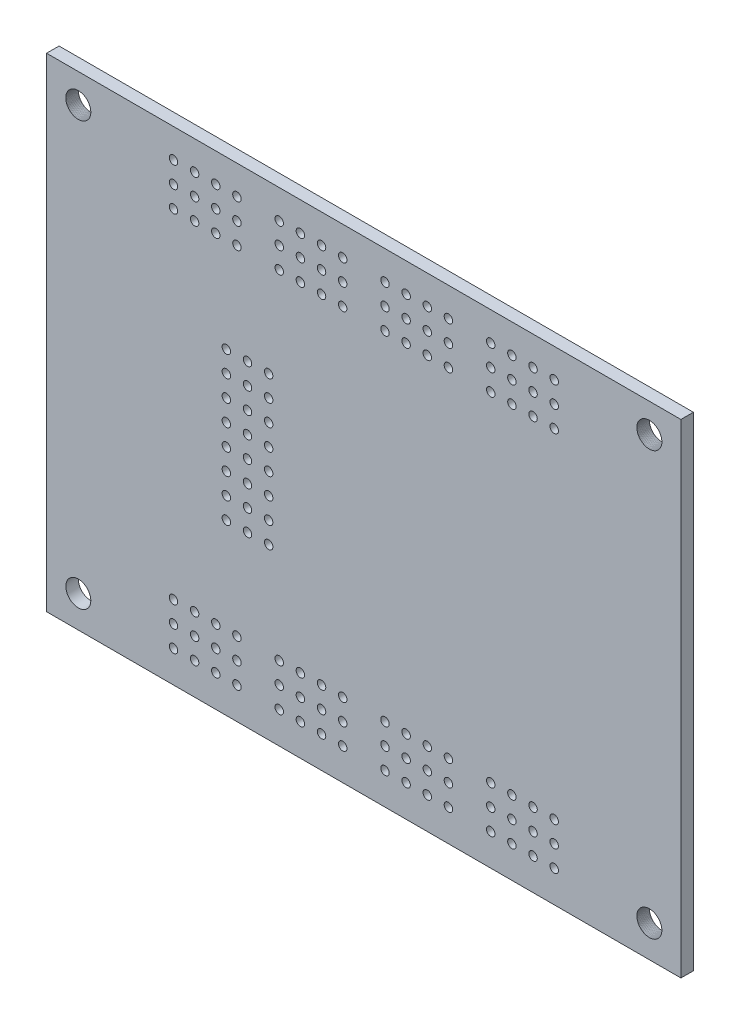
SolidWorks part; units mm, degrees
ref_plane "Front Plane" through (0, 0, 0) normal (0, 0, 1) x (1, 0, 0)
ref_plane "Top Plane" through (0, 0, 0) normal (0, 1, 0) x (1, 0, 0)
ref_plane "Right Plane" through (0, 0, 0) normal (1, 0, 0) x (0, 0, -1)
ref_plane "Plane1" through (0, 0, 1.5) normal (0, 0, 1) x (1, 0, 0)
sketch "Sketch1" plane through (0, 0, 1.5) normal (0, 0, 1) x (1, 0, 0)
  line L0 (0, 58.09) -> (0, 0)
  line L1 (0, 0) -> (76.18, 0)
  line L2 (76.18, 0) -> (76.18, 58.09)
  line L3 (76.18, 58.09) -> (0, 58.09)
  line L4 (5.3024, 54.7704) -> (5.31, 54.6636)
  line L5 (5.31, 54.6636) -> (5.31, 54.5564)
  line L6 (5.31, 54.5564) -> (5.3024, 54.4496)
  line L7 (5.3024, 54.4496) -> (5.2871, 54.3435)
  line L8 (5.2871, 54.3435) -> (5.2643, 54.2388)
  line L9 (5.2643, 54.2388) -> (5.2341, 54.136)
  line L10 (5.2341, 54.136) -> (5.1967, 54.0356)
  line L11 (5.1967, 54.0356) -> (5.1522, 53.9381)
  line L12 (5.1522, 53.9381) -> (5.1008, 53.8441)
  line L13 (5.1008, 53.8441) -> (5.0429, 53.754)
  line L14 (5.0429, 53.754) -> (4.9787, 53.6682)
  line L15 (4.9787, 53.6682) -> (4.9085, 53.5872)
  line L16 (4.9085, 53.5872) -> (4.8328, 53.5115)
  line L17 (4.8328, 53.5115) -> (4.7518, 53.4413)
  line L18 (4.7518, 53.4413) -> (4.666, 53.3771)
  line L19 (4.666, 53.3771) -> (4.5759, 53.3192)
  line L20 (4.5759, 53.3192) -> (4.4818, 53.2678)
  line L21 (4.4818, 53.2678) -> (4.3844, 53.2233)
  line L22 (4.3844, 53.2233) -> (4.284, 53.1859)
  line L23 (4.284, 53.1859) -> (4.1812, 53.1557)
  line L24 (4.1812, 53.1557) -> (4.0765, 53.1329)
  line L25 (4.0765, 53.1329) -> (3.9704, 53.1176)
  line L26 (3.9704, 53.1176) -> (3.8636, 53.11)
  line L27 (3.8636, 53.11) -> (3.7564, 53.11)
  line L28 (3.7564, 53.11) -> (3.6496, 53.1176)
  line L29 (3.6496, 53.1176) -> (3.5435, 53.1329)
  line L30 (3.5435, 53.1329) -> (3.4388, 53.1557)
  line L31 (3.4388, 53.1557) -> (3.336, 53.1859)
  line L32 (3.336, 53.1859) -> (3.2356, 53.2233)
  line L33 (3.2356, 53.2233) -> (3.1381, 53.2678)
  line L34 (3.1381, 53.2678) -> (3.0441, 53.3192)
  line L35 (3.0441, 53.3192) -> (2.954, 53.3771)
  line L36 (2.954, 53.3771) -> (2.8682, 53.4413)
  line L37 (2.8682, 53.4413) -> (2.7872, 53.5115)
  line L38 (2.7872, 53.5115) -> (2.7115, 53.5872)
  line L39 (2.7115, 53.5872) -> (2.6413, 53.6682)
  line L40 (2.6413, 53.6682) -> (2.5771, 53.754)
  line L41 (2.5771, 53.754) -> (2.5192, 53.8441)
  line L42 (2.5192, 53.8441) -> (2.4678, 53.9381)
  line L43 (2.4678, 53.9381) -> (2.4233, 54.0356)
  line L44 (2.4233, 54.0356) -> (2.3859, 54.136)
  line L45 (2.3859, 54.136) -> (2.3557, 54.2388)
  line L46 (2.3557, 54.2388) -> (2.3329, 54.3435)
  line L47 (2.3329, 54.3435) -> (2.3176, 54.4496)
  line L48 (2.3176, 54.4496) -> (2.31, 54.5564)
  line L49 (2.31, 54.5564) -> (2.31, 54.6636)
  line L50 (2.31, 54.6636) -> (2.3176, 54.7704)
  line L51 (2.3176, 54.7704) -> (2.3329, 54.8765)
  line L52 (2.3329, 54.8765) -> (2.3557, 54.9812)
  line L53 (2.3557, 54.9812) -> (2.3859, 55.084)
  line L54 (2.3859, 55.084) -> (2.4233, 55.1844)
  line L55 (2.4233, 55.1844) -> (2.4678, 55.2819)
  line L56 (2.4678, 55.2819) -> (2.5192, 55.3759)
  line L57 (2.5192, 55.3759) -> (2.5771, 55.466)
  line L58 (2.5771, 55.466) -> (2.6413, 55.5518)
  line L59 (2.6413, 55.5518) -> (2.7115, 55.6328)
  line L60 (2.7115, 55.6328) -> (2.7872, 55.7085)
  line L61 (2.7872, 55.7085) -> (2.8682, 55.7787)
  line L62 (2.8682, 55.7787) -> (2.954, 55.8429)
  line L63 (2.954, 55.8429) -> (3.0441, 55.9008)
  line L64 (3.0441, 55.9008) -> (3.1381, 55.9522)
  line L65 (3.1381, 55.9522) -> (3.2356, 55.9967)
  line L66 (3.2356, 55.9967) -> (3.336, 56.0341)
  line L67 (3.336, 56.0341) -> (3.4388, 56.0643)
  line L68 (3.4388, 56.0643) -> (3.5435, 56.0871)
  line L69 (3.5435, 56.0871) -> (3.6496, 56.1024)
  line L70 (3.6496, 56.1024) -> (3.7564, 56.11)
  line L71 (3.7564, 56.11) -> (3.8636, 56.11)
  line L72 (3.8636, 56.11) -> (3.9704, 56.1024)
  line L73 (3.9704, 56.1024) -> (4.0765, 56.0871)
  line L74 (4.0765, 56.0871) -> (4.1812, 56.0643)
  line L75 (4.1812, 56.0643) -> (4.284, 56.0341)
  line L76 (4.284, 56.0341) -> (4.3844, 55.9967)
  line L77 (4.3844, 55.9967) -> (4.4818, 55.9522)
  line L78 (4.4818, 55.9522) -> (4.5759, 55.9008)
  line L79 (4.5759, 55.9008) -> (4.666, 55.8429)
  line L80 (4.666, 55.8429) -> (4.7518, 55.7787)
  line L81 (4.7518, 55.7787) -> (4.8328, 55.7085)
  line L82 (4.8328, 55.7085) -> (4.9085, 55.6328)
  line L83 (4.9085, 55.6328) -> (4.9787, 55.5518)
  line L84 (4.9787, 55.5518) -> (5.0429, 55.466)
  line L85 (5.0429, 55.466) -> (5.1008, 55.3759)
  line L86 (5.1008, 55.3759) -> (5.1522, 55.2819)
  line L87 (5.1522, 55.2819) -> (5.1967, 55.1844)
  line L88 (5.1967, 55.1844) -> (5.2341, 55.084)
  line L89 (5.2341, 55.084) -> (5.2643, 54.9812)
  line L90 (5.2643, 54.9812) -> (5.2871, 54.8765)
  line L91 (5.2871, 54.8765) -> (5.3024, 54.7704)
  line L92 (73.8824, 54.7704) -> (73.89, 54.6636)
  line L93 (73.89, 54.6636) -> (73.89, 54.5564)
  line L94 (73.89, 54.5564) -> (73.8824, 54.4496)
  line L95 (73.8824, 54.4496) -> (73.8671, 54.3435)
  line L96 (73.8671, 54.3435) -> (73.8443, 54.2388)
  line L97 (73.8443, 54.2388) -> (73.8141, 54.136)
  line L98 (73.8141, 54.136) -> (73.7767, 54.0356)
  line L99 (73.7767, 54.0356) -> (73.7322, 53.9381)
  line L100 (73.7322, 53.9381) -> (73.6808, 53.8441)
  line L101 (73.6808, 53.8441) -> (73.6229, 53.754)
  line L102 (73.6229, 53.754) -> (73.5587, 53.6682)
  line L103 (73.5587, 53.6682) -> (73.4885, 53.5872)
  line L104 (73.4885, 53.5872) -> (73.4128, 53.5115)
  line L105 (73.4128, 53.5115) -> (73.3318, 53.4413)
  line L106 (73.3318, 53.4413) -> (73.246, 53.3771)
  line L107 (73.246, 53.3771) -> (73.1559, 53.3192)
  line L108 (73.1559, 53.3192) -> (73.0619, 53.2678)
  line L109 (73.0619, 53.2678) -> (72.9644, 53.2233)
  line L110 (72.9644, 53.2233) -> (72.864, 53.1859)
  line L111 (72.864, 53.1859) -> (72.7612, 53.1557)
  line L112 (72.7612, 53.1557) -> (72.6565, 53.1329)
  line L113 (72.6565, 53.1329) -> (72.5504, 53.1176)
  line L114 (72.5504, 53.1176) -> (72.4436, 53.11)
  line L115 (72.4436, 53.11) -> (72.3364, 53.11)
  line L116 (72.3364, 53.11) -> (72.2296, 53.1176)
  line L117 (72.2296, 53.1176) -> (72.1235, 53.1329)
  line L118 (72.1235, 53.1329) -> (72.0188, 53.1557)
  line L119 (72.0188, 53.1557) -> (71.916, 53.1859)
  line L120 (71.916, 53.1859) -> (71.8156, 53.2233)
  line L121 (71.8156, 53.2233) -> (71.7181, 53.2678)
  line L122 (71.7181, 53.2678) -> (71.6241, 53.3192)
  line L123 (71.6241, 53.3192) -> (71.534, 53.3771)
  line L124 (71.534, 53.3771) -> (71.4482, 53.4413)
  line L125 (71.4482, 53.4413) -> (71.3672, 53.5115)
  line L126 (71.3672, 53.5115) -> (71.2915, 53.5872)
  line L127 (71.2915, 53.5872) -> (71.2213, 53.6682)
  line L128 (71.2213, 53.6682) -> (71.1571, 53.754)
  line L129 (71.1571, 53.754) -> (71.0992, 53.8441)
  line L130 (71.0992, 53.8441) -> (71.0478, 53.9381)
  line L131 (71.0478, 53.9381) -> (71.0033, 54.0356)
  line L132 (71.0033, 54.0356) -> (70.9659, 54.136)
  line L133 (70.9659, 54.136) -> (70.9357, 54.2388)
  line L134 (70.9357, 54.2388) -> (70.9129, 54.3435)
  line L135 (70.9129, 54.3435) -> (70.8976, 54.4496)
  line L136 (70.8976, 54.4496) -> (70.89, 54.5564)
  line L137 (70.89, 54.5564) -> (70.89, 54.6636)
  line L138 (70.89, 54.6636) -> (70.8976, 54.7704)
  line L139 (70.8976, 54.7704) -> (70.9129, 54.8765)
  line L140 (70.9129, 54.8765) -> (70.9357, 54.9812)
  line L141 (70.9357, 54.9812) -> (70.9659, 55.084)
  line L142 (70.9659, 55.084) -> (71.0033, 55.1844)
  line L143 (71.0033, 55.1844) -> (71.0478, 55.2819)
  line L144 (71.0478, 55.2819) -> (71.0992, 55.3759)
  line L145 (71.0992, 55.3759) -> (71.1571, 55.466)
  line L146 (71.1571, 55.466) -> (71.2213, 55.5518)
  line L147 (71.2213, 55.5518) -> (71.2915, 55.6328)
  line L148 (71.2915, 55.6328) -> (71.3672, 55.7085)
  line L149 (71.3672, 55.7085) -> (71.4482, 55.7787)
  line L150 (71.4482, 55.7787) -> (71.534, 55.8429)
  line L151 (71.534, 55.8429) -> (71.6241, 55.9008)
  line L152 (71.6241, 55.9008) -> (71.7181, 55.9522)
  line L153 (71.7181, 55.9522) -> (71.8156, 55.9967)
  line L154 (71.8156, 55.9967) -> (71.916, 56.0341)
  line L155 (71.916, 56.0341) -> (72.0188, 56.0643)
  line L156 (72.0188, 56.0643) -> (72.1235, 56.0871)
  line L157 (72.1235, 56.0871) -> (72.2296, 56.1024)
  line L158 (72.2296, 56.1024) -> (72.3364, 56.11)
  line L159 (72.3364, 56.11) -> (72.4436, 56.11)
  line L160 (72.4436, 56.11) -> (72.5504, 56.1024)
  line L161 (72.5504, 56.1024) -> (72.6565, 56.0871)
  line L162 (72.6565, 56.0871) -> (72.7612, 56.0643)
  line L163 (72.7612, 56.0643) -> (72.864, 56.0341)
  line L164 (72.864, 56.0341) -> (72.9644, 55.9967)
  line L165 (72.9644, 55.9967) -> (73.0619, 55.9522)
  line L166 (73.0619, 55.9522) -> (73.1559, 55.9008)
  line L167 (73.1559, 55.9008) -> (73.246, 55.8429)
  line L168 (73.246, 55.8429) -> (73.3318, 55.7787)
  line L169 (73.3318, 55.7787) -> (73.4128, 55.7085)
  line L170 (73.4128, 55.7085) -> (73.4885, 55.6328)
  line L171 (73.4885, 55.6328) -> (73.5587, 55.5518)
  line L172 (73.5587, 55.5518) -> (73.6229, 55.466)
  line L173 (73.6229, 55.466) -> (73.6808, 55.3759)
  line L174 (73.6808, 55.3759) -> (73.7322, 55.2819)
  line L175 (73.7322, 55.2819) -> (73.7767, 55.1844)
  line L176 (73.7767, 55.1844) -> (73.8141, 55.084)
  line L177 (73.8141, 55.084) -> (73.8443, 54.9812)
  line L178 (73.8443, 54.9812) -> (73.8671, 54.8765)
  line L179 (73.8671, 54.8765) -> (73.8824, 54.7704)
  line L180 (73.8824, 3.9704) -> (73.89, 3.8636)
  line L181 (73.89, 3.8636) -> (73.89, 3.7564)
  line L182 (73.89, 3.7564) -> (73.8824, 3.6496)
  line L183 (73.8824, 3.6496) -> (73.8671, 3.5435)
  line L184 (73.8671, 3.5435) -> (73.8443, 3.4388)
  line L185 (73.8443, 3.4388) -> (73.8141, 3.336)
  line L186 (73.8141, 3.336) -> (73.7767, 3.2356)
  line L187 (73.7767, 3.2356) -> (73.7322, 3.1381)
  line L188 (73.7322, 3.1381) -> (73.6808, 3.0441)
  line L189 (73.6808, 3.0441) -> (73.6229, 2.954)
  line L190 (73.6229, 2.954) -> (73.5587, 2.8682)
  line L191 (73.5587, 2.8682) -> (73.4885, 2.7872)
  line L192 (73.4885, 2.7872) -> (73.4128, 2.7115)
  line L193 (73.4128, 2.7115) -> (73.3318, 2.6413)
  line L194 (73.3318, 2.6413) -> (73.246, 2.5771)
  line L195 (73.246, 2.5771) -> (73.1559, 2.5192)
  line L196 (73.1559, 2.5192) -> (73.0619, 2.4678)
  line L197 (73.0619, 2.4678) -> (72.9644, 2.4233)
  line L198 (72.9644, 2.4233) -> (72.864, 2.3859)
  line L199 (72.864, 2.3859) -> (72.7612, 2.3557)
  line L200 (72.7612, 2.3557) -> (72.6565, 2.3329)
  line L201 (72.6565, 2.3329) -> (72.5504, 2.3176)
  line L202 (72.5504, 2.3176) -> (72.4436, 2.31)
  line L203 (72.4436, 2.31) -> (72.3364, 2.31)
  line L204 (72.3364, 2.31) -> (72.2296, 2.3176)
  line L205 (72.2296, 2.3176) -> (72.1235, 2.3329)
  line L206 (72.1235, 2.3329) -> (72.0188, 2.3557)
  line L207 (72.0188, 2.3557) -> (71.916, 2.3859)
  line L208 (71.916, 2.3859) -> (71.8156, 2.4233)
  line L209 (71.8156, 2.4233) -> (71.7181, 2.4678)
  line L210 (71.7181, 2.4678) -> (71.6241, 2.5192)
  line L211 (71.6241, 2.5192) -> (71.534, 2.5771)
  line L212 (71.534, 2.5771) -> (71.4482, 2.6413)
  line L213 (71.4482, 2.6413) -> (71.3672, 2.7115)
  line L214 (71.3672, 2.7115) -> (71.2915, 2.7872)
  line L215 (71.2915, 2.7872) -> (71.2213, 2.8682)
  line L216 (71.2213, 2.8682) -> (71.1571, 2.954)
  line L217 (71.1571, 2.954) -> (71.0992, 3.0441)
  line L218 (71.0992, 3.0441) -> (71.0478, 3.1381)
  line L219 (71.0478, 3.1381) -> (71.0033, 3.2356)
  line L220 (71.0033, 3.2356) -> (70.9659, 3.336)
  line L221 (70.9659, 3.336) -> (70.9357, 3.4388)
  line L222 (70.9357, 3.4388) -> (70.9129, 3.5435)
  line L223 (70.9129, 3.5435) -> (70.8976, 3.6496)
  line L224 (70.8976, 3.6496) -> (70.89, 3.7564)
  line L225 (70.89, 3.7564) -> (70.89, 3.8636)
  line L226 (70.89, 3.8636) -> (70.8976, 3.9704)
  line L227 (70.8976, 3.9704) -> (70.9129, 4.0765)
  line L228 (70.9129, 4.0765) -> (70.9357, 4.1812)
  line L229 (70.9357, 4.1812) -> (70.9659, 4.284)
  line L230 (70.9659, 4.284) -> (71.0033, 4.3844)
  line L231 (71.0033, 4.3844) -> (71.0478, 4.4818)
  line L232 (71.0478, 4.4818) -> (71.0992, 4.5759)
  line L233 (71.0992, 4.5759) -> (71.1571, 4.666)
  line L234 (71.1571, 4.666) -> (71.2213, 4.7518)
  line L235 (71.2213, 4.7518) -> (71.2915, 4.8328)
  line L236 (71.2915, 4.8328) -> (71.3672, 4.9085)
  line L237 (71.3672, 4.9085) -> (71.4482, 4.9787)
  line L238 (71.4482, 4.9787) -> (71.534, 5.0429)
  line L239 (71.534, 5.0429) -> (71.6241, 5.1008)
  line L240 (71.6241, 5.1008) -> (71.7181, 5.1522)
  line L241 (71.7181, 5.1522) -> (71.8156, 5.1967)
  line L242 (71.8156, 5.1967) -> (71.916, 5.2341)
  line L243 (71.916, 5.2341) -> (72.0188, 5.2643)
  line L244 (72.0188, 5.2643) -> (72.1235, 5.2871)
  line L245 (72.1235, 5.2871) -> (72.2296, 5.3024)
  line L246 (72.2296, 5.3024) -> (72.3364, 5.31)
  line L247 (72.3364, 5.31) -> (72.4436, 5.31)
  line L248 (72.4436, 5.31) -> (72.5504, 5.3024)
  line L249 (72.5504, 5.3024) -> (72.6565, 5.2871)
  line L250 (72.6565, 5.2871) -> (72.7612, 5.2643)
  line L251 (72.7612, 5.2643) -> (72.864, 5.2341)
  line L252 (72.864, 5.2341) -> (72.9644, 5.1967)
  line L253 (72.9644, 5.1967) -> (73.0619, 5.1522)
  line L254 (73.0619, 5.1522) -> (73.1559, 5.1008)
  line L255 (73.1559, 5.1008) -> (73.246, 5.0429)
  line L256 (73.246, 5.0429) -> (73.3318, 4.9787)
  line L257 (73.3318, 4.9787) -> (73.4128, 4.9085)
  line L258 (73.4128, 4.9085) -> (73.4885, 4.8328)
  line L259 (73.4885, 4.8328) -> (73.5587, 4.7518)
  line L260 (73.5587, 4.7518) -> (73.6229, 4.666)
  line L261 (73.6229, 4.666) -> (73.6808, 4.5759)
  line L262 (73.6808, 4.5759) -> (73.7322, 4.4818)
  line L263 (73.7322, 4.4818) -> (73.7767, 4.3844)
  line L264 (73.7767, 4.3844) -> (73.8141, 4.284)
  line L265 (73.8141, 4.284) -> (73.8443, 4.1812)
  line L266 (73.8443, 4.1812) -> (73.8671, 4.0765)
  line L267 (73.8671, 4.0765) -> (73.8824, 3.9704)
  circle A0 centre (24.13, 20.32) radius 0.508
  circle A1 centre (26.67, 22.86) radius 0.508
  circle A2 centre (21.59, 22.86) radius 0.508
  circle A3 centre (24.13, 25.4) radius 0.508
  circle A4 centre (26.67, 27.94) radius 0.508
  circle A5 centre (21.59, 27.94) radius 0.508
  circle A6 centre (24.13, 30.48) radius 0.508
  circle A7 centre (26.67, 33.02) radius 0.508
  circle A8 centre (21.59, 33.02) radius 0.508
  circle A9 centre (24.13, 35.56) radius 0.508
  circle A10 centre (26.67, 38.1) radius 0.508
  circle A11 centre (21.59, 38.1) radius 0.508
  circle A12 centre (40.64, 6.35) radius 0.508
  circle A13 centre (35.56, 8.89) radius 0.508
  circle A14 centre (35.56, 3.81) radius 0.508
  circle A15 centre (33.02, 6.35) radius 0.508
  circle A16 centre (30.48, 8.89) radius 0.508
  circle A17 centre (30.48, 3.81) radius 0.508
  circle A18 centre (27.94, 6.35) radius 0.508
  circle A19 centre (22.86, 8.89) radius 0.508
  circle A20 centre (22.86, 3.81) radius 0.508
  circle A21 centre (60.96, 52.07) radius 0.508
  circle A22 centre (58.42, 54.61) radius 0.508
  circle A23 centre (58.42, 49.53) radius 0.508
  circle A24 centre (55.88, 52.07) radius 0.508
  circle A25 centre (20.32, 8.89) radius 0.508
  circle A26 centre (20.32, 3.81) radius 0.508
  circle A27 centre (53.34, 52.07) radius 0.508
  circle A28 centre (48.26, 54.61) radius 0.508
  circle A29 centre (48.26, 49.53) radius 0.508
  circle A30 centre (45.72, 52.07) radius 0.508
  circle A31 centre (43.18, 54.61) radius 0.508
  circle A32 centre (43.18, 49.53) radius 0.508
  circle A33 centre (40.64, 52.07) radius 0.508
  circle A34 centre (35.56, 54.61) radius 0.508
  circle A35 centre (35.56, 49.53) radius 0.508
  circle A36 centre (33.02, 52.07) radius 0.508
  circle A37 centre (30.48, 54.61) radius 0.508
  circle A38 centre (30.48, 49.53) radius 0.508
  circle A39 centre (27.94, 52.07) radius 0.508
  circle A40 centre (22.86, 54.61) radius 0.508
  circle A41 centre (22.86, 49.53) radius 0.508
  circle A42 centre (17.78, 6.35) radius 0.508
  circle A43 centre (20.32, 54.61) radius 0.508
  circle A44 centre (20.32, 49.53) radius 0.508
  circle A45 centre (17.78, 52.07) radius 0.508
  circle A46 centre (15.24, 54.61) radius 0.508
  circle A47 centre (15.24, 49.53) radius 0.508
  circle A48 centre (60.96, 6.35) radius 0.508
  circle A49 centre (58.42, 8.89) radius 0.508
  circle A50 centre (58.42, 3.81) radius 0.508
  circle A51 centre (55.88, 6.35) radius 0.508
  circle A52 centre (53.34, 8.89) radius 0.508
  circle A53 centre (53.34, 3.81) radius 0.508
  circle A54 centre (48.26, 6.35) radius 0.508
  circle A55 centre (45.72, 8.89) radius 0.508
  circle A56 centre (45.72, 3.81) radius 0.508
  circle A57 centre (43.18, 6.35) radius 0.508
  circle A58 centre (15.24, 8.89) radius 0.508
  circle A59 centre (15.24, 3.81) radius 0.508
  circle A60 centre (15.24, 6.35) radius 0.508
  circle A61 centre (43.18, 3.81) radius 0.508
  circle A62 centre (43.18, 8.89) radius 0.508
  circle A63 centre (45.72, 6.35) radius 0.508
  circle A64 centre (48.26, 3.81) radius 0.508
  circle A65 centre (48.26, 8.89) radius 0.508
  circle A66 centre (53.34, 6.35) radius 0.508
  circle A67 centre (55.88, 3.81) radius 0.508
  circle A68 centre (55.88, 8.89) radius 0.508
  circle A69 centre (58.42, 6.35) radius 0.508
  circle A70 centre (60.96, 3.81) radius 0.508
  circle A71 centre (60.96, 8.89) radius 0.508
  circle A72 centre (15.24, 52.07) radius 0.508
  circle A73 centre (17.78, 49.53) radius 0.508
  circle A74 centre (17.78, 54.61) radius 0.508
  circle A75 centre (20.32, 52.07) radius 0.508
  circle A76 centre (17.78, 3.81) radius 0.508
  circle A77 centre (17.78, 8.89) radius 0.508
  circle A78 centre (22.86, 52.07) radius 0.508
  circle A79 centre (27.94, 49.53) radius 0.508
  circle A80 centre (27.94, 54.61) radius 0.508
  circle A81 centre (30.48, 52.07) radius 0.508
  circle A82 centre (33.02, 49.53) radius 0.508
  circle A83 centre (33.02, 54.61) radius 0.508
  circle A84 centre (35.56, 52.07) radius 0.508
  circle A85 centre (40.64, 49.53) radius 0.508
  circle A86 centre (40.64, 54.61) radius 0.508
  circle A87 centre (43.18, 52.07) radius 0.508
  circle A88 centre (45.72, 49.53) radius 0.508
  circle A89 centre (45.72, 54.61) radius 0.508
  circle A90 centre (48.26, 52.07) radius 0.508
  circle A91 centre (53.34, 49.53) radius 0.508
  circle A92 centre (53.34, 54.61) radius 0.508
  circle A93 centre (20.32, 6.35) radius 0.508
  circle A94 centre (55.88, 49.53) radius 0.508
  circle A95 centre (55.88, 54.61) radius 0.508
  circle A96 centre (58.42, 52.07) radius 0.508
  circle A97 centre (60.96, 49.53) radius 0.508
  circle A98 centre (60.96, 54.61) radius 0.508
  circle A99 centre (22.86, 6.35) radius 0.508
  circle A100 centre (27.94, 3.81) radius 0.508
  circle A101 centre (27.94, 8.89) radius 0.508
  circle A102 centre (30.48, 6.35) radius 0.508
  circle A103 centre (33.02, 3.81) radius 0.508
  circle A104 centre (33.02, 8.89) radius 0.508
  circle A105 centre (35.56, 6.35) radius 0.508
  circle A106 centre (40.64, 3.81) radius 0.508
  circle A107 centre (40.64, 8.89) radius 0.508
  circle A108 centre (24.13, 38.1) radius 0.508
  circle A109 centre (21.59, 35.56) radius 0.508
  circle A110 centre (26.67, 35.56) radius 0.508
  circle A111 centre (24.13, 33.02) radius 0.508
  circle A112 centre (21.59, 30.48) radius 0.508
  circle A113 centre (26.67, 30.48) radius 0.508
  circle A114 centre (24.13, 27.94) radius 0.508
  circle A115 centre (21.59, 25.4) radius 0.508
  circle A116 centre (26.67, 25.4) radius 0.508
  circle A117 centre (24.13, 22.86) radius 0.508
  circle A118 centre (21.59, 20.32) radius 0.508
  circle A119 centre (26.67, 20.32) radius 0.508
  circle A120 centre (3.81, 3.81) radius 1.5
extrude "Boss-Extrude1" add sketch "Sketch1" against normal blind 1.5
